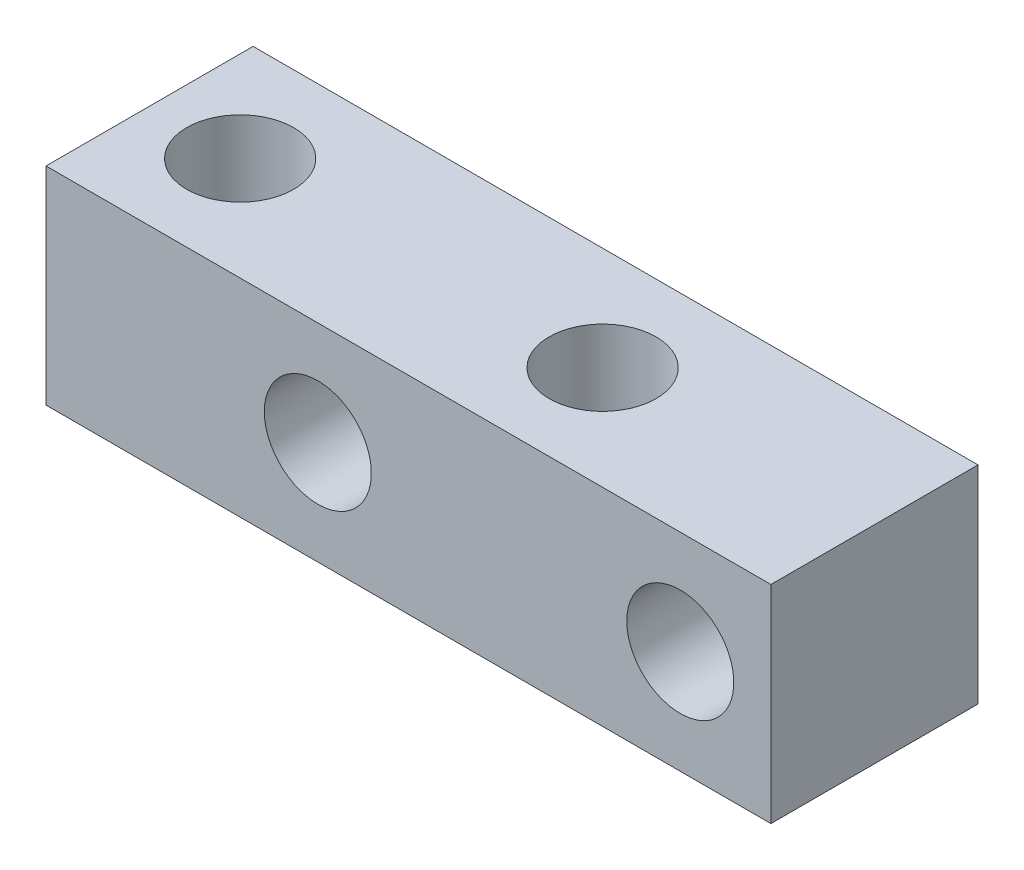
SolidWorks part; units mm, degrees
material "灰铸铁"
ref_plane "前视基准面" through (0, 0, 0) normal (0, 0, 1) x (1, 0, 0)
ref_plane "上视基准面" through (0, 0, 0) normal (0, 1, 0) x (1, 0, 0)
ref_plane "右视基准面" through (0, 0, 0) normal (1, 0, 0) x (0, 0, -1)
other "Configuration Table"
sketch "草图1" plane through (0, 0, 0) normal (0, 1, 0) x (1, 0, 0)
  line L1 (-10.5, -3) -> (10.5, -3)
  line L2 (-10.5, -3) -> (-10.5, 3)
  line L3 (-10.5, 3) -> (10.5, 3)
  line L4 (10.5, -3) -> (10.5, 3)
  line L5 (-10.5, -3) -> (10.5, 3) construction
  line L6 (-10.5, 3) -> (10.5, -3) construction
  point P0 (0, 0)
  dimension "D1" = 6
  dimension "D2" = 21
extrude "凸台-拉伸1" add sketch "草图1" along normal blind 6
sketch "草图2" plane through (0, 0, -3) normal (0, 0, -1) x (-1, 0, 0)
  line L0 (-10.5, 3) -> (12.0148, 3) construction
  line L1 (-10.5, 6) -> (-10.5, 0) construction
  circle A0 centre (-7.875, 3) radius 1.55
  circle A1 centre (2.625, 3) radius 1.55
  dimension "D1" = 3.1
  dimension "D2" = 3.1
  dimension "D3" = 2.625
  dimension "D4" = 10.5
extrude "切除-拉伸1" cut sketch "草图2" against normal up to surface (6 mm away) up to face at (0, 3, 3)
sketch "草图3" plane through (0, 0, 0) normal (0, -1, 0) x (1, 0, 0)
  line L0 (-10.5, 0) -> (13.9477, 0) construction
  line L1 (-10.5, -3) -> (-10.5, 3) construction
  circle A0 centre (-7.875, 0) radius 1.55
  circle A1 centre (2.625, 0) radius 1.55
  dimension "D1" = 3.1
  dimension "D2" = 3.1
  dimension "D3" = 2.625
  dimension "D4" = 10.5
extrude "切除-拉伸2" cut sketch "草图3" against normal up to surface (6 mm away) up to face at (0, 6, 0)
